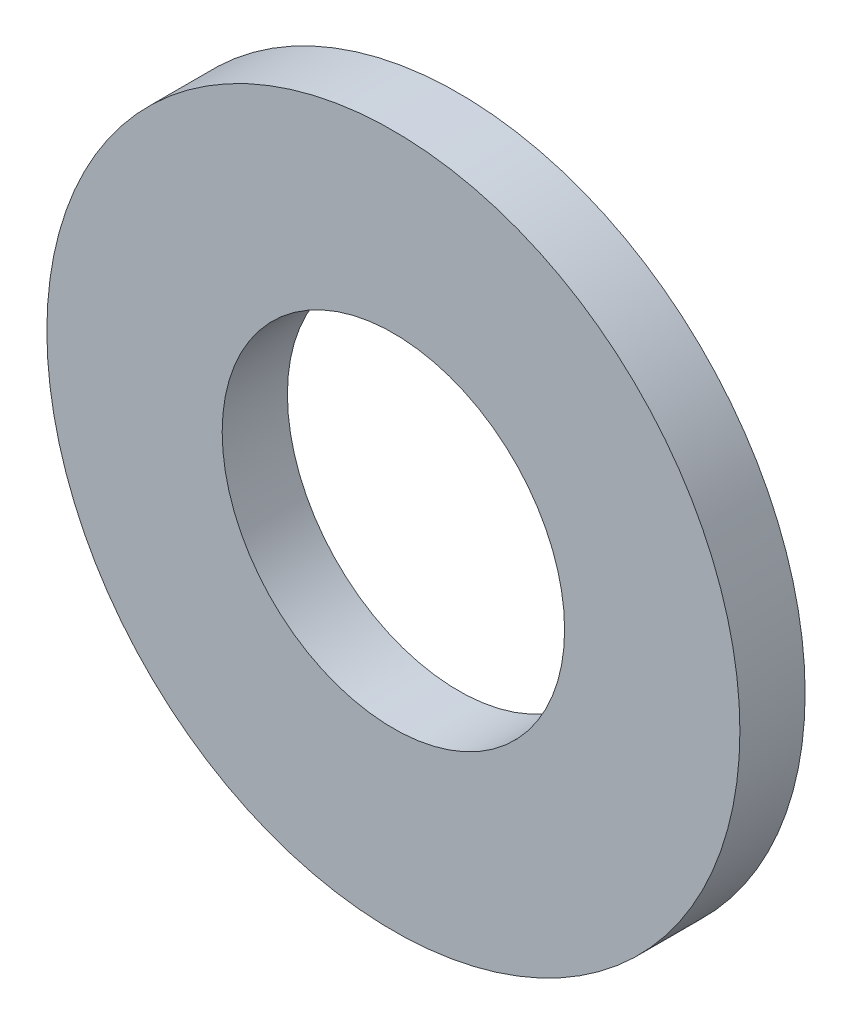
SolidWorks part; units mm, degrees
ref_plane "Спереди" through (0, 0, 0) normal (0, 0, 1) x (1, 0, 0)
ref_plane "Сверху" through (0, 0, 0) normal (0, 1, 0) x (1, 0, 0)
ref_plane "Справа" through (0, 0, 0) normal (1, 0, 0) x (0, 0, -1)
sketch "Эскиз1" plane through (0, 0, 0) normal (0, 0, 1) x (1, 0, 0)
  circle A0 centre (0, 0) radius 4.2
  circle A1 centre (0, 0) radius 8.5
  dimension "D1" = 17
  dimension "D2" = 8.4
extrude "Вытянуть1" add sketch "Эскиз1" along normal blind 1.6
